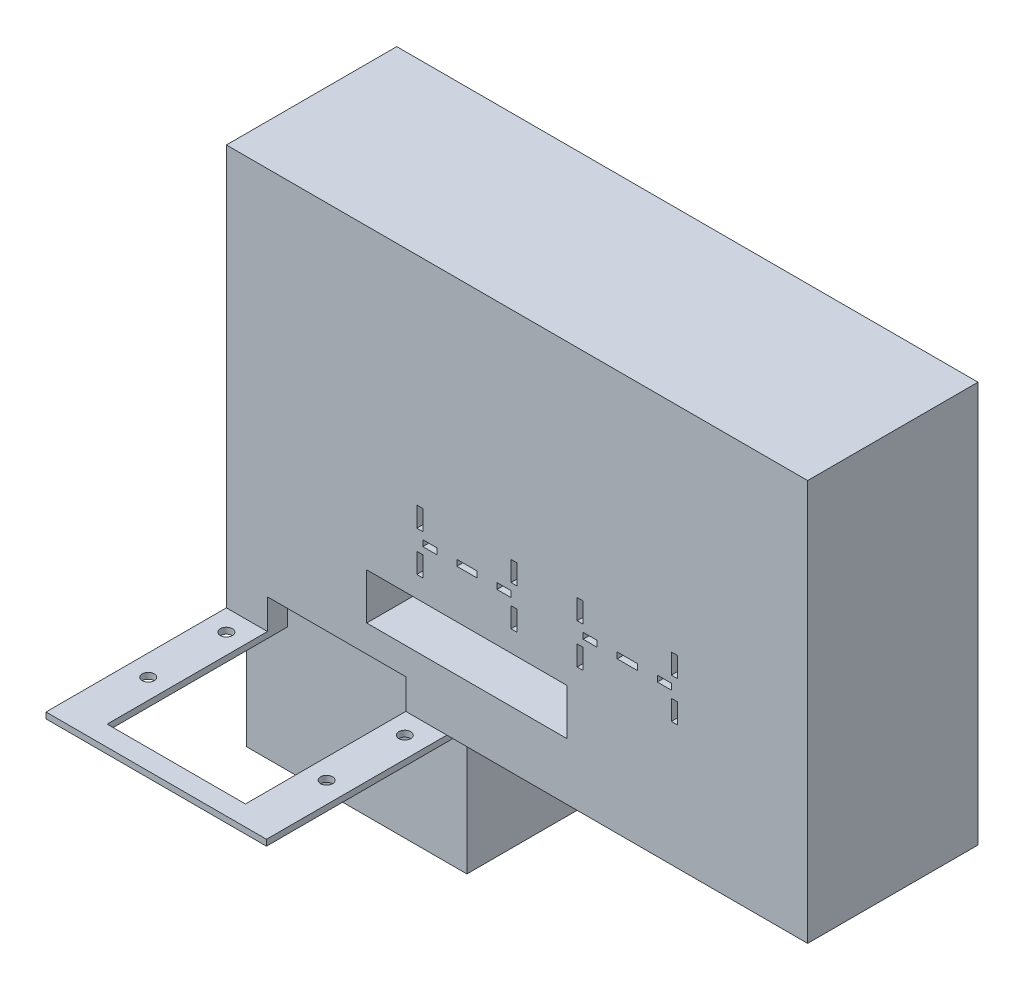
SolidWorks part; units mm, degrees
material "Cedro"
ref_plane "Alzado" through (0, 0, 0) normal (0, 0, 1) x (1, 0, 0)
ref_plane "Planta" through (0, 0, 0) normal (0, 1, 0) x (1, 0, 0)
ref_plane "Vista lateral" through (0, 0, 0) normal (1, 0, 0) x (0, 0, -1)
sketch "Croquis1" plane through (0, 0, 0) normal (0, 0, 1) x (1, 0, 0)
  line L1 (-85.6349, 58.6584) -> (24.3651, 58.6584)
  line L2 (-85.6349, 58.6584) -> (-85.6349, -6.3416)
  line L3 (-85.6349, -6.3416) -> (24.3651, -6.3416)
  line L4 (24.3651, 58.6584) -> (24.3651, -6.3416)
  line L5 (-85.6349, 58.6584) -> (24.3651, -6.3416) construction
  line L6 (-85.6349, -6.3416) -> (24.3651, 58.6584) construction
  point P0 (-30.6349, 26.1584)
  dimension "D1" = 65
  dimension "D2" = 110
extrude "Saliente-Extruir1" add sketch "Croquis1" along normal blind 75
sketch "Croquis3" plane through (0, 0, 75) normal (0, 0, 1) x (1, 0, 0)
  line L0 (-85.6349, 58.6584) -> (24.3651, 58.6584)
  line L1 (-85.6349, 58.6584) -> (-85.6349, 55.6584)
  line L2 (-85.6349, 58.6584) -> (-85.6349, -6.3416) construction
  line L3 (-85.6349, 55.6584) -> (24.3651, 55.6584)
  line L4 (24.3651, -6.3416) -> (24.3651, 58.6584) construction
  line L5 (24.3651, 55.6584) -> (24.3651, 58.6584)
  dimension "D1" = 3
extrude "Saliente-Extruir2" add sketch "Croquis3" along normal blind 70
sketch "Croquis4" plane through (0, 55.6584, 0) normal (0, -1, 0) x (1, 0, 0)
  line L3 (-65.1349, 134.5) -> (-65.1349, 75)
  line L6 (-85.6349, 75) -> (24.3651, 75) construction
  line L7 (-65.1349, 134.5) -> (-65.1349, 145)
  line L8 (-85.6349, 145) -> (24.3651, 145) construction
  line L9 (-65.1349, 75) -> (3.8651, 75)
  line L11 (-65.1349, 145) -> (3.8651, 145)
  line L13 (3.8651, 138) -> (3.8651, 145)
  line L14 (3.8651, 138) -> (3.8651, 75)
  circle A0 centre (-75.1349, 134.5) radius 3
  circle A1 centre (-75.1349, 95.5) radius 3
  circle A2 centre (13.8651, 134.5) radius 3
  circle A3 centre (13.8651, 95.5) radius 3
  dimension "D5" = 6
  dimension "D6" = 6
  dimension "D7" = 6
  dimension "D8" = 6
  dimension "D1" = 10
  dimension "D3" = 39
  dimension "D4" = 89
extrude "Cortar-Extruir1" cut sketch "Croquis4" against normal blind 70
sketch "Croquis6" plane through (0, 58.6584, 0) normal (0, 1, 0) x (1, 0, 0)
  line L0 (-85.6349, -145) -> (-85.6349, -175)
  line L1 (-85.6349, -175) -> (24.3651, -175)
  line L2 (24.3651, -175) -> (24.3651, -145)
  line L3 (24.3651, -145) -> (3.8651, -145)
  line L4 (-65.1349, -145) -> (-65.1349, -165)
  line L5 (-65.1349, -165) -> (3.8651, -165)
  line L6 (3.8651, -165) -> (3.8651, -145)
  line L7 (-65.1349, -145) -> (-85.6349, -145)
  dimension "D1" = 30
  dimension "D2" = 20
extrude "Saliente-Extruir3" add sketch "Croquis6" against normal blind 3
sketch "Croquis7" plane through (0, 58.6584, 0) normal (0, 1, 0) x (1, 0, 0)
  line L0 (-85.6349, 0) -> (204.3651, 0)
  line L1 (-85.6349, 0) -> (-85.6349, -85)
  line L2 (-85.6349, -175) -> (-85.6349, 0) construction
  line L3 (-85.6349, -85) -> (204.3651, -85)
  line L4 (204.3651, -85) -> (204.3651, 0)
  dimension "D1" = 290
  dimension "D2" = 85
extrude "Saliente-Extruir4" add sketch "Croquis7" along normal blind 200
sketch "Croquis8" plane through (0, 0, 85) normal (0, 0, 1) x (1, 0, 0)
  line L0 (-65.1349, 58.6584) -> (-65.1349, 73.6584)
  line L1 (-65.1349, 73.6584) -> (3.8651, 73.6584)
  line L2 (3.8651, 58.6584) -> (3.8651, 73.6584)
  line L3 (-65.1349, 58.6584) -> (3.8651, 58.6584)
  dimension "D1" = 15
  dimension "D2" = 15
extrude "Cortar-Extruir2" cut sketch "Croquis8" against normal blind 10
sketch "Croquis10" plane through (0, 0, 85) normal (0, 0, 1) x (1, 0, 0)
  line L1 (-0.6349, 87.0942) -> (-15.6349, 87.0942)
  line L2 (69.3651, 87.0942) -> (-0.6349, 87.0942)
  line L4 (-15.6349, 87.0942) -> (-15.6349, 110.0942)
  line L5 (-15.6349, 110.0942) -> (-0.6349, 110.0942)
  line L6 (69.3651, 87.0942) -> (84.3651, 87.0942)
  line L7 (69.3651, 110.0942) -> (-0.6349, 110.0942)
  line L8 (84.3651, 87.0942) -> (84.3651, 110.0942)
  line L11 (84.3651, 110.0942) -> (69.3651, 110.0942)
  dimension "D1" = 15
  dimension "D3" = 15
extrude "Cortar-Extruir3" cut sketch "Croquis10" against normal blind 50
sketch "Croquis12" plane through (0, 0, 85) normal (0, 0, 1) x (1, 0, 0)
  line L0 (34.3651, 110.0942) -> (34.3651, 258.6584) construction
  line L1 (84.3651, 110.0942) -> (-15.6349, 110.0942) construction
  line L2 (-85.6349, 258.6584) -> (204.3651, 258.6584) construction
  line L3 (34.3651, 110.0942) -> (34.3651, 134.0942) construction
  line L4 (12.3651, 134.0942) -> (19.3651, 134.0942)
  line L5 (12.3651, 130.5942) -> (12.3651, 120.5942)
  line L6 (56.3651, 140.5942) -> (59.3651, 140.5942)
  line L7 (9.3651, 120.5942) -> (9.3651, 130.5942)
  line L8 (12.3651, 120.5942) -> (9.3651, 120.5942)
  line L9 (12.3651, 134.0942) -> (12.3651, 130.5942) construction
  line L10 (56.3651, 140.5942) -> (56.3651, 150.5942)
  line L11 (12.3651, 137.0942) -> (12.3651, 140.5942) construction
  line L12 (56.3651, 130.5942) -> (56.3651, 120.5942)
  line L13 (56.3651, 134.0942) -> (49.3651, 134.0942)
  line L14 (34.3651, 162.0942) -> (34.3651, 137.0942) construction
  line L15 (12.3651, 150.5942) -> (9.3651, 150.5942)
  line L16 (12.3651, 135.5942) -> (9.3651, 135.5942) construction
  line L17 (12.3651, 140.5942) -> (9.3651, 140.5942)
  line L18 (59.3651, 150.5942) -> (59.3651, 140.5942)
  line L19 (56.3651, 130.5942) -> (59.3651, 130.5942)
  line L20 (29.3651, 134.0942) -> (39.3651, 134.0942)
  line L21 (56.3651, 135.5942) -> (59.3651, 135.5942) construction
  line L22 (12.3651, 130.5942) -> (9.3651, 130.5942)
  line L23 (56.3651, 137.0942) -> (56.3651, 140.5942) construction
  line L24 (19.3651, 134.0942) -> (19.3651, 137.0942)
  line L25 (39.3651, 134.0942) -> (49.3651, 134.0942) construction
  line L26 (39.3651, 137.0942) -> (29.3651, 137.0942)
  line L27 (49.3651, 134.0942) -> (49.3651, 137.0942)
  line L28 (39.3651, 134.0942) -> (39.3651, 137.0942)
  line L29 (12.3651, 140.5942) -> (12.3651, 150.5942)
  line L30 (29.3651, 134.0942) -> (19.3651, 134.0942) construction
  line L31 (49.3651, 137.0942) -> (56.3651, 137.0942)
  line L32 (56.3651, 137.0942) -> (56.3651, 134.0942)
  line L33 (56.3651, 150.5942) -> (59.3651, 150.5942)
  line L34 (9.3651, 150.5942) -> (9.3651, 140.5942)
  line L35 (59.3651, 120.5942) -> (59.3651, 130.5942)
  line L36 (56.3651, 134.0942) -> (56.3651, 130.5942) construction
  line L37 (19.3651, 137.0942) -> (12.3651, 137.0942)
  line L38 (12.3651, 137.0942) -> (12.3651, 134.0942)
  line L39 (119.3651, 137.0942) -> (109.3651, 137.0942)
  line L42 (129.3651, 137.0942) -> (136.3651, 137.0942)
  line L43 (92.3651, 150.5942) -> (89.3651, 150.5942)
  line L44 (92.3651, 135.5942) -> (89.3651, 135.5942) construction
  line L45 (89.3651, 120.5942) -> (89.3651, 130.5942)
  line L46 (92.3651, 134.0942) -> (99.3651, 134.0942)
  line L47 (92.3651, 120.5942) -> (89.3651, 120.5942)
  line L48 (119.3651, 134.0942) -> (129.3651, 134.0942) construction
  line L49 (136.3651, 150.5942) -> (139.3651, 150.5942)
  line L50 (136.3651, 134.0942) -> (136.3651, 130.5942) construction
  line L51 (129.3651, 134.0942) -> (129.3651, 137.0942)
  line L52 (136.3651, 130.5942) -> (139.3651, 130.5942)
  line L53 (99.3651, 137.0942) -> (92.3651, 137.0942)
  line L54 (139.3651, 120.5942) -> (139.3651, 130.5942)
  line L55 (109.3651, 134.0942) -> (119.3651, 134.0942)
  line L56 (92.3651, 140.5942) -> (89.3651, 140.5942)
  line L57 (92.3651, 137.0942) -> (92.3651, 134.0942)
  line L58 (136.3651, 140.5942) -> (136.3651, 150.5942)
  line L59 (92.3651, 130.5942) -> (92.3651, 120.5942)
  line L60 (136.3651, 130.5942) -> (136.3651, 120.5942)
  line L61 (92.3651, 130.5942) -> (89.3651, 130.5942)
  line L62 (99.3651, 134.0942) -> (99.3651, 137.0942)
  line L63 (92.3651, 134.0942) -> (92.3651, 130.5942) construction
  line L64 (139.3651, 150.5942) -> (139.3651, 140.5942)
  line L65 (89.3651, 150.5942) -> (89.3651, 140.5942)
  line L66 (119.3651, 134.0942) -> (119.3651, 137.0942)
  line L67 (92.3651, 140.5942) -> (92.3651, 150.5942)
  line L68 (92.3651, 137.0942) -> (92.3651, 140.5942) construction
  line L69 (136.3651, 120.5942) -> (139.3651, 120.5942)
  line L70 (136.3651, 135.5942) -> (139.3651, 135.5942) construction
  line L71 (136.3651, 140.5942) -> (139.3651, 140.5942)
  line L72 (136.3651, 137.0942) -> (136.3651, 140.5942) construction
  line L73 (136.3651, 137.0942) -> (136.3651, 134.0942)
  line L74 (109.3651, 134.0942) -> (109.3651, 137.0942)
  line L75 (109.3651, 134.0942) -> (99.3651, 134.0942) construction
  line L76 (136.3651, 134.0942) -> (129.3651, 134.0942)
  line L77 (56.3651, 120.5942) -> (59.3651, 120.5942)
  line L78 (29.3651, 134.0942) -> (29.3651, 137.0942)
  line L79 (59.3651, 135.5942) -> (89.3651, 135.5942) construction
  point P10 (34.3651, 184.3763)
  point P14 (34.3651, 134.0942)
  point P40 (34.3651, 187.3763)
  point P46 (114.3651, 134.0942)
  point P76 (114.3651, 137.0942)
  point P81 (34.3651, 137.0942)
  dimension "D2" = 24
  dimension "D3" = 25
  dimension "D4" = 5
  dimension "D5" = 3
  dimension "D6" = 10
  dimension "D7" = 7
  dimension "D8" = 3.5
  dimension "D9" = 3
  dimension "D10" = 5
  dimension "D13" = 3
  dimension "D14" = 10
  dimension "D15" = 7
  dimension "D16" = 3.5
  dimension "D17" = 3
  dimension "D18" = 10
  dimension "D19" = 3
  dimension "D20" = 10
  dimension "D21" = 3
  dimension "D22" = 30
extrude "Cortar-Extruir4" cut sketch "Croquis12" against normal blind 3
